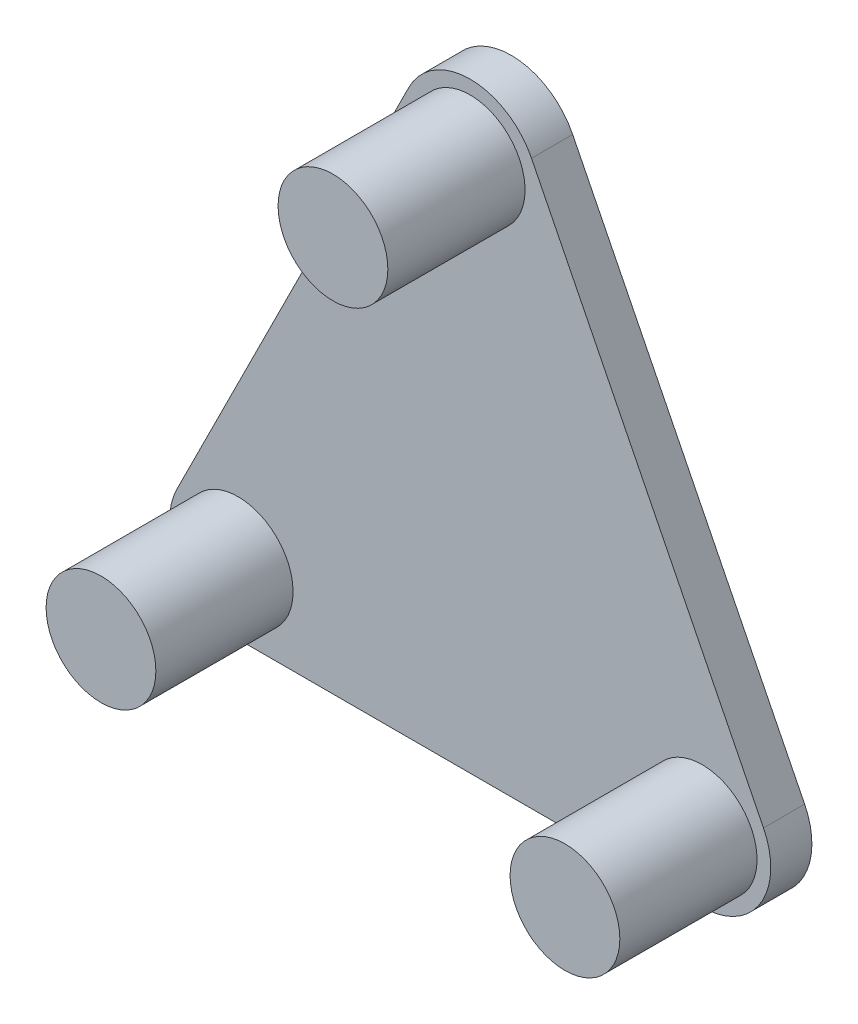
SolidWorks part; units mm, degrees
ref_plane "Alzado" through (0, 0, 0) normal (0, 0, 1) x (1, 0, 0)
ref_plane "Planta" through (0, 0, 0) normal (0, 1, 0) x (1, 0, 0)
ref_plane "Vista lateral" through (0, 0, 0) normal (1, 0, 0) x (0, 0, -1)
sketch "Croquis1" plane through (0, 0, 0) normal (0, 0, 1) x (1, 0, 0)
  line L0 (-10.3631, 26.6845) -> (-10.3631, -17.1352) construction
  line L1 (-27.2729, -17.1352) -> (6.5468, -17.1352)
  line L2 (-31.745, -9.8991) -> (-14.8352, 23.9205)
  line L3 (-5.8909, 23.9205) -> (11.0189, -9.8991)
  line L4 (-10.3631, 4.7746) -> (-31.5262, -14.7638) construction
  line L5 (-10.3631, 4.7746) -> (10.8, -14.7638) construction
  arc A8 (-27.2729, -17.1352) -> (-31.745, -9.8991) centre (-27.2729, -12.1352) cw
  arc A9 (6.5468, -17.1352) -> (11.0189, -9.8991) centre (6.5468, -12.1352) ccw
  arc A10 (-14.8352, 23.9205) -> (-5.8909, 23.9205) centre (-10.3631, 21.6845) cw
  point P2 (-35.3631, -17.1352)
  point P6 (-10.3631, -2.1352)
  point P9 (-10.3631, -17.1352)
  point P10 (14.6369, -17.1352)
  point P13 (-10.3631, 32.8648)
  dimension "D1" = 50
  dimension "D3" = 5
  dimension "D2" = 50
extrude "Saliente-Extruir1" add sketch "Croquis1" along normal blind 3
sketch "Croquis2" plane through (0, 0, 3) normal (0, 0, 1) x (1, 0, 0)
  circle A0 centre (-10.3631, 21.6845) radius 4
  circle A1 centre (-27.2729, -12.1352) radius 4
  circle A2 centre (6.5468, -12.1352) radius 4
  dimension "D1" = 8
  dimension "D2" = 8
  dimension "D3" = 8
extrude "Saliente-Extruir2" add sketch "Croquis2" along normal blind 10
